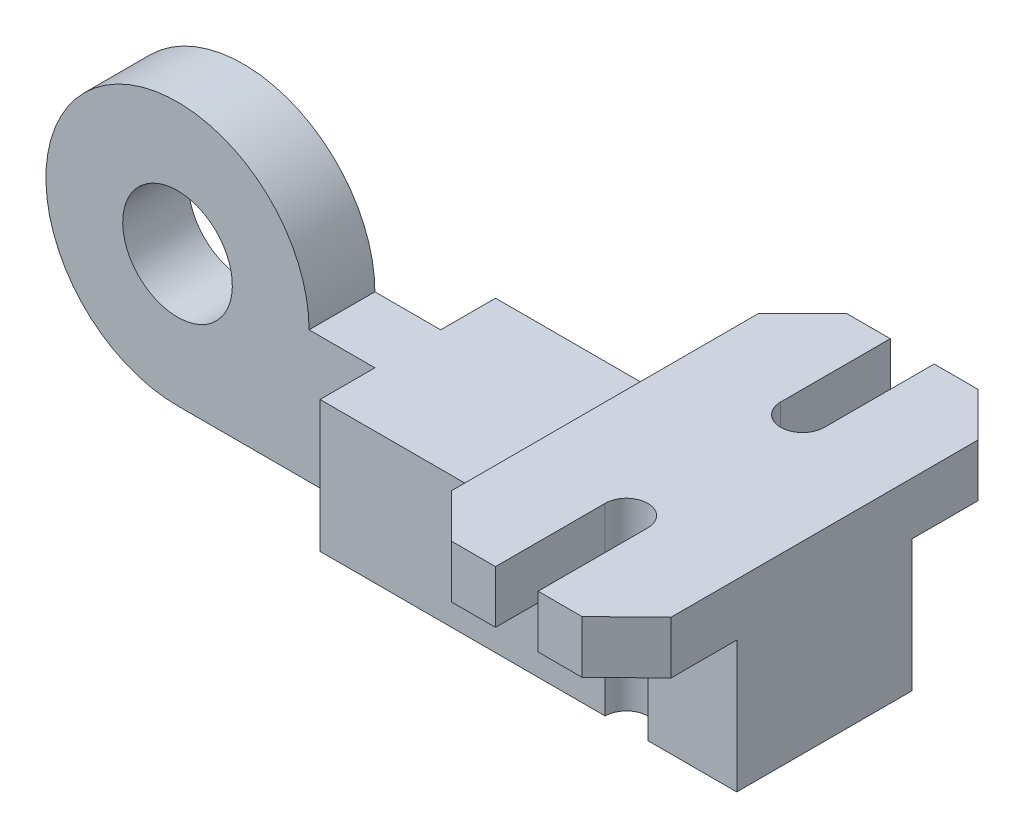
SolidWorks part; units mm, degrees
ref_plane "Front Plane" through (0, 0, 0) normal (0, 0, 1) x (1, 0, 0)
ref_plane "Top Plane" through (0, 0, 0) normal (0, 1, 0) x (1, 0, 0)
ref_plane "Right Plane" through (0, 0, 0) normal (1, 0, 0) x (0, 0, -1)
sketch "Sketch1" plane through (0, 0, 0) normal (0, 1, 0) x (1, 0, 0)
  line L0 (-32.5813, 24.4306) -> (-42.5813, 24.4306)
  line L1 (-42.5813, 24.4306) -> (-52.5813, 14.4306)
  line L2 (-52.5813, 14.4306) -> (-52.5813, -55.5694)
  line L3 (-52.5813, -55.5694) -> (-42.5813, -65.5694)
  line L4 (-42.5813, -65.5694) -> (-32.5813, -65.5694)
  line L6 (-32.5813, -65.5694) -> (-32.5813, -40.5694)
  line L8 (-22.5813, 24.4306) -> (-22.5813, -0.5694)
  line L9 (-32.5813, 24.4306) -> (-32.5813, -0.5694)
  line L10 (-22.87, -65.5694) -> (-22.87, -40.5694)
  line L11 (-12.87, -65.5694) -> (-22.87, -65.5694)
  line L12 (-2.5813, -55.5694) -> (-12.87, -65.5694)
  line L13 (-2.5813, 14.4306) -> (-2.5813, -55.5694)
  line L14 (-12.5813, 24.4306) -> (-2.5813, 14.4306)
  line L15 (-22.5813, 24.4306) -> (-12.5813, 24.4306)
  arc A0 (-32.5813, -0.5694) -> (-22.5813, -0.5694) centre (-27.5813, -0.5694) ccw
  arc A1 (-22.87, -40.5694) -> (-32.5813, -40.5694) centre (-27.7256, -40.5694) ccw
  dimension "D3" = 5
  dimension "D1" = 90
  dimension "D2" = 25
  dimension "D4" = 25
  dimension "D5" = 45
  dimension "D6" = 20
  dimension "D7" = 20
  dimension "D8" = 10
  dimension "D9" = 10
  dimension "D10" = 10
  dimension "D11" = 10
  dimension "D12" = 10
  dimension "D13" = 10
  dimension "D15" = 20
  dimension "D16" = 25
extrude "Boss-Extrude1" add sketch "Sketch1" along normal blind 12
sketch "Sketch3" plane through (-2.5813, 0, 0) normal (1, 0, 0) x (0, 0, -1)
  line L0 (-55.5694, 0) -> (14.4306, 0) construction
  line L1 (-40.5694, 0) -> (-0.5694, 0)
  line L2 (-40.5694, 0) -> (-40.5694, -30)
  line L3 (-40.5694, -30) -> (-0.5694, -30)
  line L4 (-0.5694, 0) -> (-0.5694, -30)
  point P6 (0, 0)
  point P11 (0, 0)
  dimension "D2" = 30
  dimension "D3" = 40
extrude "Boss-Extrude2" add sketch "Sketch3" against normal blind 95
sketch "Sketch5" plane through (0, 12, 0) normal (0, 1, 0) x (1, 0, 0)
  line L0 (-32.5813, -0.5694) -> (-22.5813, -0.5694) construction
  line L1 (-32.5813, -40.5694) -> (-22.87, -40.5694) construction
  circle A0 centre (-27.5813, -0.5694) radius 5
  circle A1 centre (-27.7256, -40.5694) radius 4.8557
extrude "Cut-Extrude1" cut sketch "Sketch5" against normal blind 95
ref_plane "Plane1" through (0, 0, 13.0694) normal (0, 0, -1) x (-1, 0, 0)
sketch "Sketch7" plane through (0, 0, 13.0694) normal (0, 0, -1) x (-1, 0, 0)
  line L0 (97.5813, 0) -> (112.5813, 0)
  line L1 (97.5813, -30) -> (142.5813, -30)
  line L2 (97.5813, 0) -> (97.5813, -30)
  arc A0 (142.5813, -30) -> (112.5813, 0) centre (142.5813, 0) ccw
  circle A1 centre (142.5813, 0) radius 12.5
  dimension "D2" = 60
  dimension "D4" = 25
  dimension "D1" = 15
extrude "Boss-Extrude3" add sketch "Sketch7" against normal blind 15
